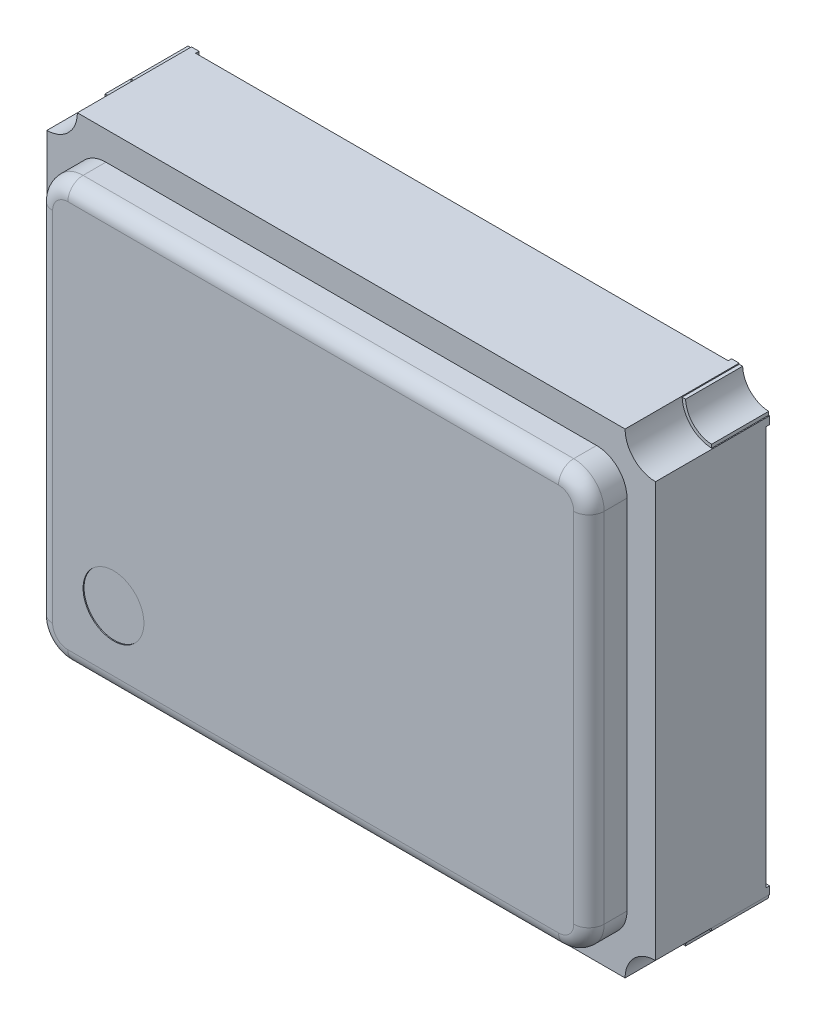
SolidWorks part; units mm, degrees
ref_plane "Front Plane" through (0, 0, 0) normal (0, 0, 1) x (1, 0, 0)
ref_plane "Top Plane" through (0, 0, 0) normal (0, 1, 0) x (1, 0, 0)
ref_plane "Right Plane" through (0, 0, 0) normal (1, 0, 0) x (0, 0, -1)
sketch "Sketch1" plane through (0, 0, 0) normal (0, 0, 1) x (1, 0, 0)
  line L1 (-1.6, 1.25) -> (1.6, 1.25)
  line L2 (-1.6, 1.25) -> (-1.6, -1.25)
  line L3 (-1.6, -1.25) -> (1.6, -1.25)
  line L4 (1.6, 1.25) -> (1.6, -1.25)
  line L5 (-1.6, 1.25) -> (1.6, -1.25) construction
  line L6 (-1.6, -1.25) -> (1.6, 1.25) construction
  point P0 (0, 0)
  dimension "D1" = 3.2
  dimension "D2" = 2.5
extrude "Boss-Extrude1" add sketch "Sketch1" along normal blind 0.564 contours L1 L4 L3 L2
sketch "Sketch2" plane through (0, 0, 0) normal (0, 0, -1) x (-1, 0, 0)
  line L17 (0.6, -0.8) -> (-0.6, -0.8) construction
  line L18 (1.5, -1.15) -> (0.6, -1.15)
  line L19 (1.5, -1.15) -> (1.5, -0.45)
  line L20 (1.5, -0.45) -> (0.6, -0.45)
  line L21 (0.6, -1.15) -> (0.6, -0.45)
  line L22 (-0.6, -1.15) -> (-1.5, -1.15)
  line L23 (-0.6, -1.15) -> (-0.6, -0.45)
  line L24 (-0.6, -0.45) -> (-1.5, -0.45)
  line L25 (-1.5, -1.15) -> (-1.5, -0.45)
  line L26 (-0.6, 0.45) -> (-1.5, 0.45)
  line L27 (-0.6, 0.45) -> (-0.6, 1.15)
  line L28 (-0.6, 1.15) -> (-1.5, 1.15)
  line L29 (-1.5, 0.45) -> (-1.5, 1.15)
  line L30 (1.5, 0.45) -> (0.6, 0.45)
  line L31 (1.5, 0.45) -> (1.5, 1.15)
  line L32 (1.5, 1.15) -> (0.6, 1.15)
  line L33 (0.6, 0.45) -> (0.6, 1.15)
  line L34 (-1.05, -0.45) -> (-1.05, 0.45) construction
  line L35 (1.6, -1.25) -> (-1.6, -1.25) construction
  line L36 (-1.6, 1.25) -> (-1.6, -1.25) construction
  line L37 (1.4, -1.15) -> (1.4, -1.25)
  line L38 (1.5, -1.05) -> (1.6, -1.05)
  line L39 (1.6, 1.25) -> (1.6, -1.25) construction
  line L40 (1.6, -1.05) -> (1.6, -1.25)
  line L41 (1.6, -1.25) -> (1.4, -1.25)
  line L42 (-1.4, -1.15) -> (-1.4, -1.25)
  line L43 (-1.4, -1.25) -> (-1.6, -1.25)
  line L44 (-1.6, -1.25) -> (-1.6, -1.05)
  line L45 (-1.6, -1.05) -> (-1.5, -1.05)
  line L46 (-1.5, 1.05) -> (-1.6, 1.05)
  line L47 (-1.6, 1.05) -> (-1.6, 1.25)
  line L48 (-1.6, 1.25) -> (-1.4, 1.25)
  line L49 (1.6, 1.25) -> (-1.6, 1.25) construction
  line L50 (-1.4, 1.25) -> (-1.4, 1.15)
  line L51 (1.4, 1.15) -> (1.4, 1.25)
  line L52 (1.4, 1.25) -> (1.6, 1.25)
  line L53 (1.6, 1.25) -> (1.6, 1.05)
  line L54 (1.6, 1.05) -> (1.5, 1.05)
  line L55 (-1.4, -1.15) -> (-1.5, -1.15)
  line L56 (-1.5, -1.15) -> (-1.5, -1.05)
  line L57 (-1.4, 1.15) -> (-1.5, 1.15)
  line L58 (-1.5, 1.15) -> (-1.5, 1.05)
  line L59 (1.5, 1.05) -> (1.5, 1.15)
  line L60 (1.5, 1.15) -> (1.4, 1.15)
  line L61 (1.4, -1.15) -> (1.5, -1.15)
  line L62 (1.5, -1.15) -> (1.5, -1.05)
  point P20 (-1.05, 0)
  point P22 (0, -0.8)
  line M8 (1.6, -1.25) -> (1.6, 1.25)
  line M9 (1.6, 1.25) -> (-1.6, 1.25)
  line M10 (-1.6, 1.25) -> (-1.6, -1.25)
  line M11 (-1.6, -1.25) -> (1.6, -1.25)
  dimension "D1" = 0.9
  dimension "D2" = 0.7
  dimension "D3" = 1.2
  dimension "D4" = 0.9
  dimension "D5" = 0.1
  dimension "D6" = 0.1
  dimension "D7" = 0.2
extrude "Boss-Extrude2" add sketch "Sketch2" along normal blind 0.018 contours L21 L18 L19 L20 | L38 L19 L18 L37 M11 M8 | L25 L22 L23 L24 | L45 L42 L22 L25 M10 M11 | L50 L46 L29 L28 M9 M10 | L29 L26 L27 L28 | L33 L30 L31 L32 | L54 L51 L32 L31 M8 M9
chamfer "Chamfer2" distance 0.25 angle 45 1 edges at (-0.6, -0.45, -0.009)
sketch "Sketch3" plane through (0, 0, 0) normal (0, 0, -1) x (-1, 0, 0)
  line L0 (1.44, -1.25) -> (-1.44, -1.25) construction
  line L1 (1.4, -1.25) -> (-1.4, -1.25) construction
  line L2 (1.6, -1.09) -> (1.6, 1.09) construction
  line L3 (1.6, 1.05) -> (1.6, -1.05) construction
  line L4 (1.44, 1.25) -> (-1.44, 1.25) construction
  line L5 (1.4, 1.25) -> (-1.4, 1.25) construction
  line L6 (-1.6, -1.09) -> (-1.6, 1.09) construction
  line L7 (-1.6, 1.05) -> (-1.6, -1.05) construction
  line L8 (1.6, 1.09) -> (1.6, 1.25)
  line L9 (1.6, 1.25) -> (1.44, 1.25)
  line L10 (-1.44, 1.25) -> (-1.6, 1.25)
  line L11 (-1.6, 1.25) -> (-1.6, 1.09)
  line L12 (-1.6, -1.09) -> (-1.6, -1.25)
  line L13 (-1.6, -1.25) -> (-1.44, -1.25)
  line L14 (1.6, -1.09) -> (1.6, -1.25)
  line L15 (1.6, -1.25) -> (1.44, -1.25)
  arc A0 (1.6, -1.09) -> (1.44, -1.25) centre (1.6, -1.25) ccw
  arc A1 (-1.44, -1.25) -> (-1.6, -1.09) centre (-1.6, -1.25) ccw
  arc A2 (-1.44, 1.25) -> (-1.6, 1.09) centre (-1.6, 1.25) cw
  arc A3 (1.6, 1.09) -> (1.44, 1.25) centre (1.6, 1.25) cw
  point P16 (0, -1.25)
  point P17 (0, 1.25)
  point P19 (-1.6, 0)
  point P20 (1.6, 0)
  dimension "D1" = 0.16
extrude "Cut-Extrude1" cut sketch "Sketch3" against normal through all both and the other way through all
sketch "Sketch5" plane through (0, 0, 0) normal (0, 0, -1) x (-1, 0, 0)
  line L0 (1.4401, -1.245) -> (1.4581, -1.245)
  line L1 (1.595, -1.0901) -> (1.595, -1.1081)
  line L2 (1.4, -1.25) -> (-1.4, -1.25) construction
  arc A0 (1.595, -1.0901) -> (1.4401, -1.245) centre (1.6, -1.25) ccw
  arc A1 (1.6, -1.09) -> (1.44, -1.25) centre (1.6, -1.25) ccw construction
  arc A2 (1.595, -1.1081) -> (1.4581, -1.245) centre (1.6, -1.25) ccw
  arc A3 (1.6, -1.09) -> (1.44, -1.25) centre (1.6, -1.25) ccw construction
  point P15 (1.4869, -1.1369)
  point P19 (1.4869, -1.1369)
  dimension "D2" = 0.005
extrude "Boss-Extrude3" add sketch "Sketch5" against normal blind 0.282 and the other way through all
mirror "Mirror1" about plane through (0, 0, 0) normal (1, 0, 0) of "Boss-Extrude3"
mirror "Mirror2" about plane through (0, 0, 0) normal (0, 1, 0) of "Mirror1", "Boss-Extrude3"
sketch "Sketch7" plane through (0, 0, 0.564) normal (0, 0, 1) x (1, 0, 0)
  line L0 (-1.6, 1.09) -> (-1.6, -1.09) construction
  line L1 (-1.44, 1.25) -> (1.44, 1.25)
  line L2 (1.6, 1.09) -> (1.6, -1.09)
  line L3 (1.44, -1.25) -> (-1.44, -1.25)
  line L4 (-1.6, -1.09) -> (-1.6, 1.09)
  arc A0 (-1.6, -1.09) -> (-1.44, -1.25) centre (-1.6, -1.25) cw
  arc A1 (-1.44, -1.25) -> (-1.6, -1.09) centre (-1.6, -1.25) ccw construction
  arc A2 (1.44, -1.25) -> (1.6, -1.09) centre (1.6, -1.25) cw
  arc A3 (1.6, -1.09) -> (1.44, -1.25) centre (1.6, -1.25) ccw construction
  arc A4 (1.44, 1.25) -> (1.6, 1.09) centre (1.6, 1.25) ccw
  arc A5 (1.44, 1.25) -> (1.6, 1.09) centre (1.6, 1.25) ccw construction
  arc A6 (-1.44, 1.25) -> (-1.6, 1.09) centre (-1.6, 1.25) cw
  arc A7 (-1.6, 1.09) -> (-1.44, 1.25) centre (-1.6, 1.25) ccw construction
extrude "Boss-Extrude4" add sketch "Sketch7" along normal blind 0.018
sketch "Sketch8" plane through (0, 0, 0.582) normal (0, 0, 1) x (1, 0, 0)
  line L0 (-1.6, 1.09) -> (-1.6, -1.09) construction
  line L1 (-1.45, 1.1) -> (1.45, 1.1)
  line L2 (-1.45, 1.1) -> (-1.45, -1.1)
  line L3 (-1.45, -1.1) -> (1.45, -1.1)
  line L4 (1.45, 1.1) -> (1.45, -1.1)
  line L5 (-1.45, 1.1) -> (1.45, -1.1) construction
  line L6 (-1.45, -1.1) -> (1.45, 1.1) construction
  line L7 (1.44, 1.25) -> (-1.44, 1.25) construction
  point P0 (0, 0)
  dimension "D1" = 0.15
  dimension "D2" = 0.15
extrude "Boss-Extrude5" add sketch "Sketch8" along normal blind 0.2
fillet "Fillet1" radius 0.16 4 edges at (-1.45, 1.1, 0.682) (1.45, 1.1, 0.682) (1.45, -1.1, 0.682) (-1.45, -1.1, 0.682)
fillet "Fillet2" radius 0.08 8 edges at (1.4031, 1.0531, 0.782) (1.45, 0, 0.782) (1.4031, -1.0531, 0.782) (0, -1.1, 0.782) (-1.4031, -1.0531, 0.782) (-1.45, 0, 0.782) (-1.4031, 1.0531, 0.782) (0, 1.1, 0.782)
sketch "Sketch9" plane through (0, 0, 0.782) normal (0, 0, 1) x (1, 0, 0)
  line L1 (-1.37, 0.94) -> (-1.37, -0.94) construction
  line L2 (-1.29, -1.02) -> (1.29, -1.02) construction
  circle A0 centre (-1.05, -0.7) radius 0.16
  point P2 (-1.05, -0.86)
  point P3 (-1.21, -0.7)
  dimension "D1" = 0.32
  dimension "D2" = 0.16
  dimension "D3" = 0.16
extrude "Cut-Extrude2" cut sketch "Sketch9" against normal blind 0.005
equation "\"W\"= 3.2"
equation "\"L\"= 2.5"
equation "\"D1@Sketch1\"=\"W\""
equation "\"D2@Sketch1\"=\"L\""
equation "\"H\"= 0.8"
equation "\"D1@Boss-Extrude1\"=\"H_base\""
equation "\"H_shield\"= 0.2"
equation "\"H_contact\"= 0.018"
equation "\"H_base\"= \"H\" - \"H_shield\" - 2 * \"H_contact\""
equation "\"X_contact_spacing\"= 1.2"
equation "\"Y_contact_spacing\"= 0.9"
equation "\"W_contact\"= 0.9"
equation "\"L_contact\"= 0.7"
equation "\"D1@Sketch2\"=\"W_contact\""
equation "\"D2@Sketch2\"=\"L_contact\""
equation "\"D3@Sketch2\"=\"X_contact_spacing\""
equation "\"D4@Sketch2\"=\"Y_contact_spacing\""
equation "\"D1@Boss-Extrude2\"=\"H_contact\""
equation "\"Chamfer_contact\"= 0.25"
equation "\"D1@Chamfer2\"=\"Chamfer_contact\""
equation "\"R\"=0.16"
equation "\"D7@Sketch2\"=\"R\"*1.25"
equation "\"D1@Sketch5\"=\"H_contact\""
equation "\"D1@Boss-Extrude3\"=\"H_base\"/2"
equation "\"D1@Sketch3\"=\"R\""
equation "\"D1@Boss-Extrude4\"=\"H_contact\""
equation "\"D2@Sketch8\"=\"D1@Sketch8\""
equation "\"D1@Boss-Extrude5\"=\"H_shield\""
equation "\"D1@Fillet1\"=\"R\""
equation "\"D1@Fillet2\"=\"R\"/2"
equation "\"D2@Sketch9\"=\"D1@Sketch9\"/2"
equation "\"D3@Sketch9\"=\"D2@Sketch9\""
